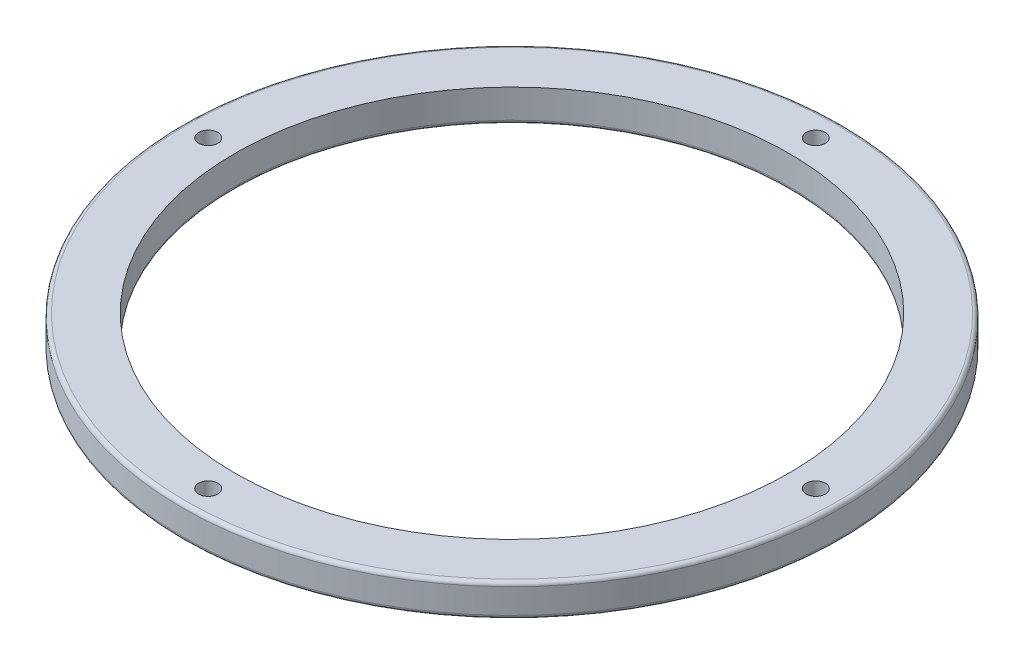
SolidWorks part; units mm, degrees
material "6061 Alloy"
ref_plane "Front Plane" through (0, 0, 0) normal (0, 0, 1) x (1, 0, 0)
ref_plane "Top Plane" through (0, 0, 0) normal (0, 1, 0) x (1, 0, 0)
ref_plane "Right Plane" through (0, 0, 0) normal (1, 0, 0) x (0, 0, -1)
sketch "Sketch1" plane through (0, 0, 0) normal (0, 1, 0) x (1, 0, 0)
  circle A0 centre (0, 0) radius 72.5
  circle A1 centre (0, 0) radius 86.25
  dimension "D1" = 145
  dimension "D2" = 172.5
extrude "Boss-Extrude1" add sketch "Sketch1" along normal blind 8.5
fillet "Fillet1" radius 1 3 edges at (0, 8.5, 86.25) (0, 0, 72.5) (0, 0, 86.25)
sketch "Sketch2" plane through (0, 8.5, 0) normal (0, 1, 0) x (1, 0, 0)
  circle A0 centre (0, 0) radius 79.5 construction
  point P3 (0, 79.5)
  point P4 (-79.5, 0)
  point P6 (0, -79.5)
  point P8 (79.5, 0)
  dimension "D1" = 159
hole_wizard "M6 Tapped Hole1" positions "Sketch5" profile "Sketch6" tap size "M6" standard "ISO" end condition through all
sketch "Sketch5" plane through (0, 8.5, 0) normal (0, 1, 0) x (1, 0, 0)
  point P0 (0, 79.5)
  point P3 (79.5, 0)
  point P6 (0, -79.5)
  point P9 (-79.5, 0)
sketch "Sketch6" plane through (0, 8.5, -79.5) normal (1, 0, 0) x (0, 0, 1)
  line L0 (0, 0) -> (0, 8.5)
  line L1 (0, 8.5) -> (2.5, 8.5)
  line L2 (2.5, 8.5) -> (2.5, 0)
  line L5 (2.5, 0) -> (0, 0)
  line L11 (0, -6.35) -> (0, 107.95) construction
  dimension "Thru Tap Drill Dia." = 5
  dimension "Thru Tap Drill Depth" = 8.5
cosmetic thread "Hole Thread1"
cosmetic thread "Hole Thread2"
cosmetic thread "Hole Thread3"
cosmetic thread "Hole Thread4"
